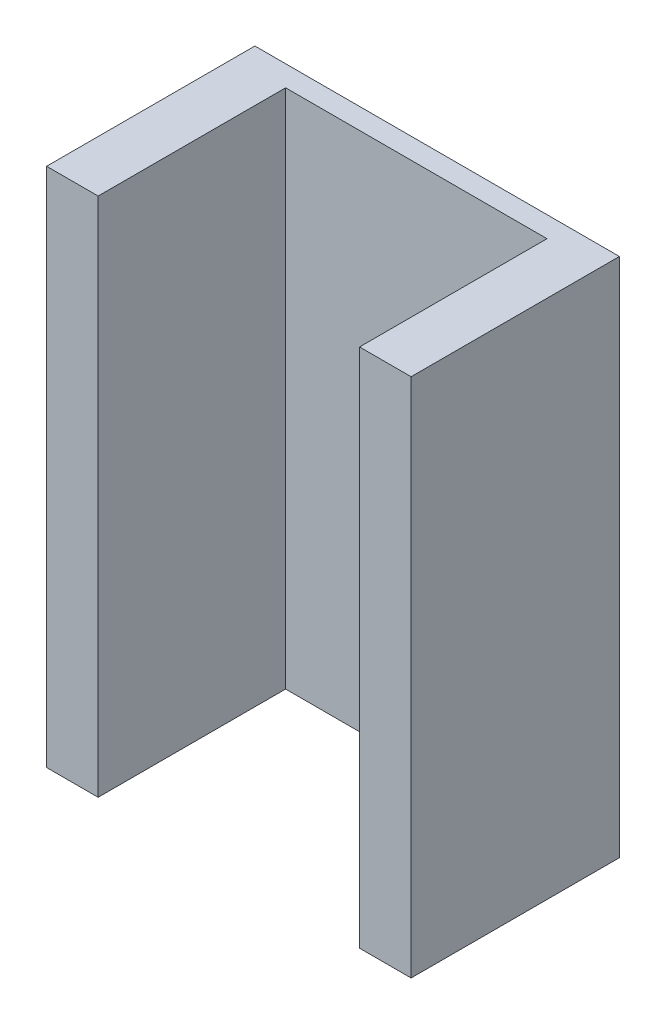
SolidWorks part; units mm, degrees
ref_plane "前视基准面" through (0, 0, 0) normal (0, 0, 1) x (1, 0, 0)
ref_plane "上视基准面" through (0, 0, 0) normal (0, 1, 0) x (1, 0, 0)
ref_plane "右视基准面" through (0, 0, 0) normal (1, 0, 0) x (0, 0, -1)
sketch "草图1" plane through (0, 0, 0) normal (0, 0, 1) x (1, 0, 0)
  line L1 (0, 0) -> (70, 0)
  line L2 (0, 0) -> (0, 100)
  line L3 (0, 100) -> (70, 100)
  line L4 (70, 0) -> (70, 100)
  dimension "D1" = 70
  dimension "D2" = 100
extrude "凸台-拉伸1" add sketch "草图1" along normal blind 40
sketch "草图2" plane through (0, 0, 40) normal (0, 0, 1) x (1, 0, 0)
  line L0 (70, 100) -> (0, 100) construction
  line L1 (9.9, 100) -> (60.1, 100)
  line L2 (9.9, 100) -> (9.9, 0)
  line L3 (9.9, 0) -> (60.1, 0)
  line L4 (60.1, 100) -> (60.1, 0)
  line L5 (0, 0) -> (70, 0) construction
  line L6 (0, 100) -> (0, 0) construction
  line L7 (70, 0) -> (70, 100) construction
  dimension "D1" = 9.9
  dimension "D2" = 9.9
extrude "切除-拉伸1" cut sketch "草图2" against normal blind 36
sketch "草图3" plane through (0, 0, 0) normal (0, 0, -1) x (-1, 0, 0)
  line L0 (-70, 0) -> (-70, 100) construction
  line L1 (0, 0) -> (-70, 0) construction
  circle A0 centre (-35, 50) radius 1.5
  dimension "D1" = 3
  dimension "D2" = 35
  dimension "D3" = 50
extrude "切除-拉伸2" cut sketch "草图3" against normal up to next
sketch "草图4" plane through (0.0031, 0, 0.3572) normal (0.0087, 0, 1) x (1, 0, -0.0087)
  circle A0 centre (35.0964, 42.9137) radius 0.8
  circle A1 centre (28.094, 49.9113) radius 0.8
  circle A2 centre (35.0917, 56.9137) radius 0.8
  circle A3 centre (42.094, 49.9161) radius 0.8
  dimension "D1" = 1.6
  dimension "D2" = 1.6
  dimension "D3" = 1.6
sketch "草图6" plane through (0, 0, 4) normal (0, 0, 1) x (1, 0, 0)
  circle A0 centre (35.0982, 42.9137) radius 0.8
  circle A1 centre (28.0961, 49.9113) radius 0.8
  circle A2 centre (35.0934, 56.9137) radius 0.8
  circle A3 centre (42.0955, 49.9161) radius 0.8
  dimension "D1" = 1.5999
  dimension "D2" = 1.5999
  dimension "D3" = 1.5999
  dimension "D4" = 1.5999
extrude "切除-拉伸4" cut sketch "草图6" against normal up to next
